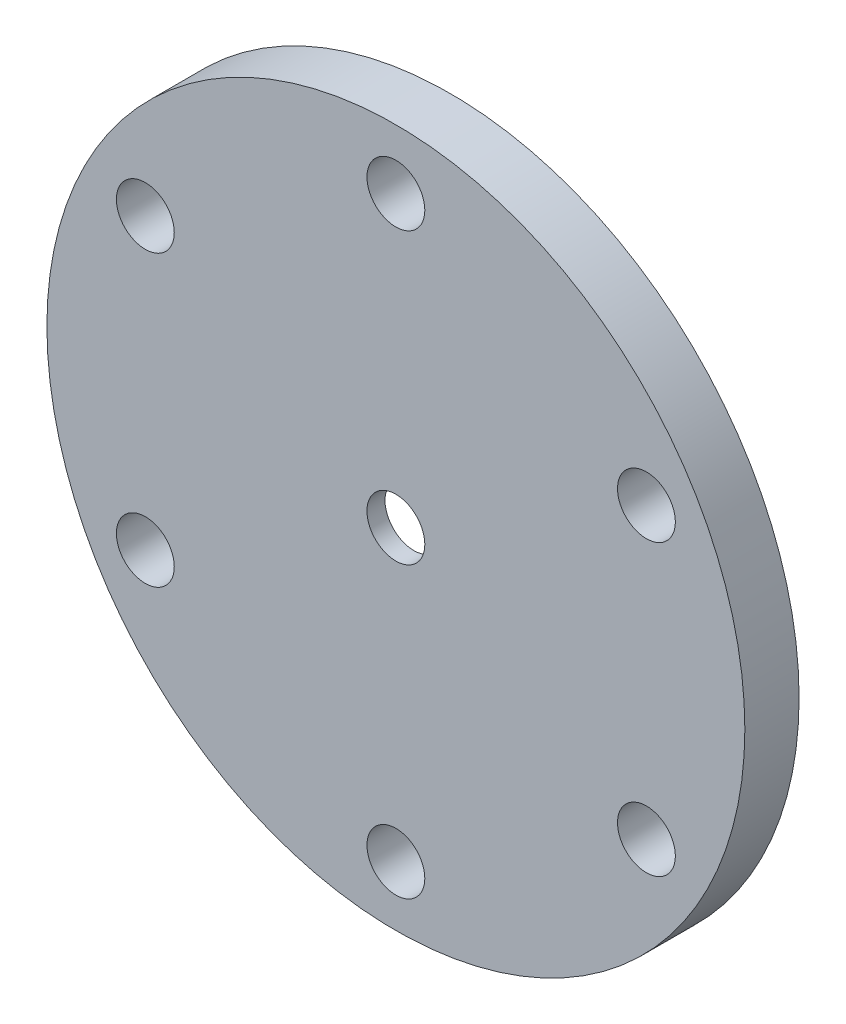
SolidWorks part; units mm, degrees
ref_plane "Front" through (0, 0, 0) normal (0, 0, 1) x (1, 0, 0)
ref_plane "Top" through (0, 0, 0) normal (0, 1, 0) x (1, 0, 0)
ref_plane "Right" through (0, 0, 0) normal (1, 0, 0) x (0, 0, -1)
sketch "Croquis1" plane through (0, 0, 0) normal (0, 0, 1) x (1, 0, 0)
  line L0 (0, -55) -> (0, 55) construction
  line L1 (55, 0) -> (-55, 0) construction
  circle A0 centre (0, 0) radius 19.3
  circle A1 centre (0, 16) radius 1.6
  circle A2 centre (0, 0) radius 1.6
  circle A3 centre (13.8564, 8) radius 1.6
  circle A4 centre (13.8564, -8) radius 1.6
  circle A5 centre (0, -16) radius 1.6
  circle A6 centre (-13.8564, -8) radius 1.6
  circle A7 centre (-13.8564, 8) radius 1.6
  dimension "D1" = 38.6
  dimension "D2" = 3.2
  dimension "D3" = 16
  dimension "D4" = 6
extrude "Saliente-Extruir1" add sketch "Croquis1" along normal mid plane 3
sketch "Croquis2" plane through (0, 0, -1.5) normal (0, 0, -1) x (-1, 0, 0)
  circle A0 centre (0, 0) radius 12
  circle A1 centre (0, 0) radius 1.6 construction
  circle A2 centre (0, 0) radius 1.6
  dimension "D1" = 24
extrude "Cortar-Extruir1" cut sketch "Croquis2" against normal blind 2
